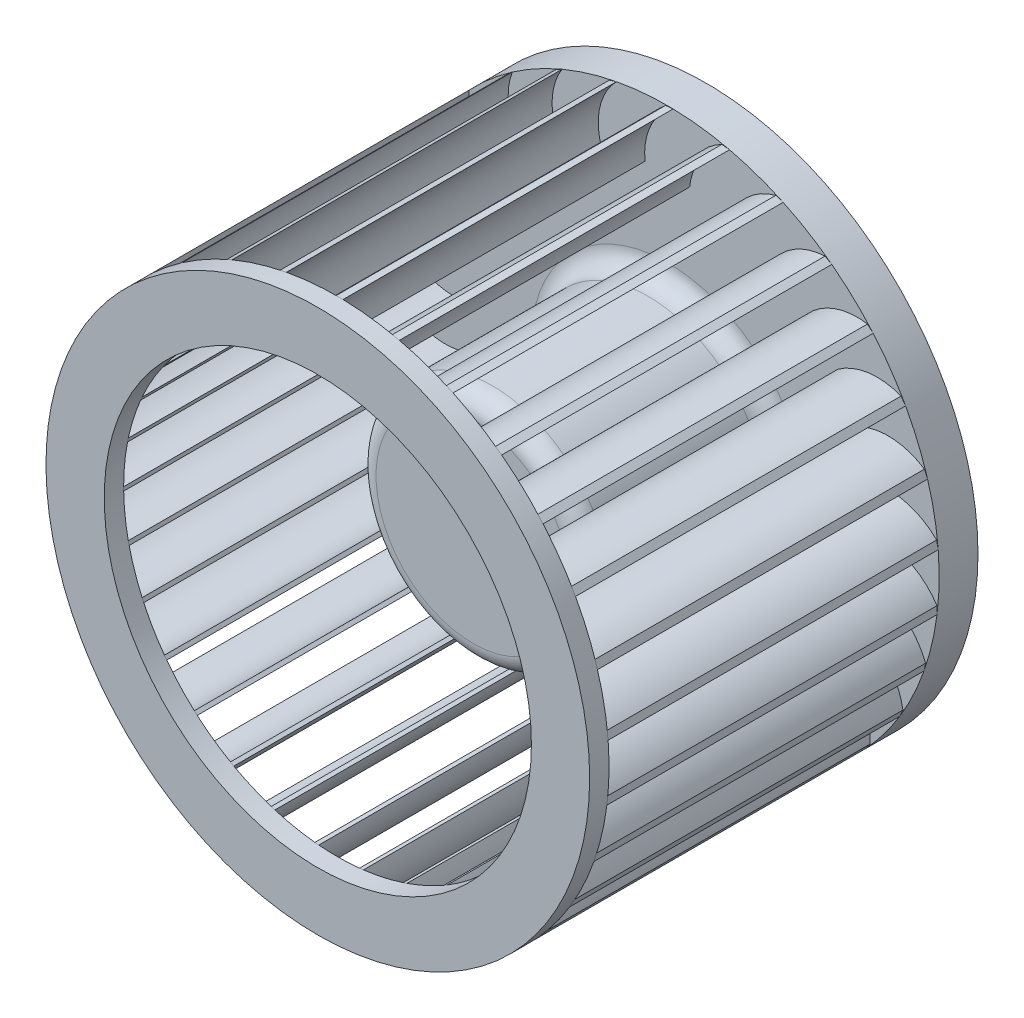
SolidWorks part; units mm, degrees
material "Silicon"
ref_plane "Front Plane" through (0, 0, 0) normal (0, 0, 1) x (1, 0, 0)
ref_plane "Top Plane" through (0, 0, 0) normal (0, 1, 0) x (1, 0, 0)
ref_plane "Right Plane" through (0, 0, 0) normal (1, 0, 0) x (0, 0, -1)
sketch "Sketch1" plane through (0, 0, 0) normal (0, 0, 1) x (1, 0, 0)
  circle A0 centre (0, 0) radius 14 construction
  dimension "D1" = 28
sketch "Sketch2" plane through (0, 0, 0) normal (0, 0, 1) x (1, 0, 0)
  circle A0 centre (0, 0) radius 14
  dimension "D1" = 28
extrude "Boss-Extrude1" add sketch "Sketch2" along normal blind 2
ref_plane "Plane1" through (0, 14, 0) normal (0, 1, 0) x (1, 0, 0)
ref_plane "Plane3" through (0, 13, 0) normal (0, 1, 0) x (1, 0, 0)
sketch "Sketch3" plane through (0, 13, 0) normal (0, 1, 0) x (1, 0, 0)
  line L0 (-14, -2) -> (14, -2) construction
  arc A0 (0, 0) -> (0, -2) centre (-36, -1) cw
  arc A1 (0, 0) -> (0, -2) centre (-54.9909, -1) cw
  dimension "D2" = 55
  dimension "D1" = 36
ref_plane "Plane2" through (0, 25, 0) normal (0, 1, 0) x (1, 0, 0)
sketch "Sketch4" plane through (0, 25, 0) normal (0, 1, 0) x (1, 0, 0)
  arc A0 (0, 0) -> (0, -2) centre (-32.2345, -1) cw
  arc A1 (0, 0) -> (0, -2) centre (-44.7388, -1) cw
  dimension "D1" = 32.25
  dimension "D2" = 44.75
sketch "Sketch5" plane through (0, 0, 2) normal (0, 0, 1) x (1, 0, 0)
  line L0 (0.0091, 13) -> (0, 13) construction
  line L1 (0, 0) -> (0, 13) construction
  line L2 (0, 13) -> (0, 14) construction
  line L3 (3.3352, 20.4911) -> (-3.3352, 5.5089) construction
  circle A0 centre (0, 0) radius 14 construction
  spline S0 degree 2 poles (0, 13) (1.6676, 16.7455) (0, 14) knots 0 0 0 1 1 1
  dimension "D1" = 8.2
  dimension "D2" = 24
sketch "Sketch6" plane through (0, 0, 0) normal (0, 0, -1) x (-1, 0, 0)
  circle A0 centre (0, 0) radius 14
  dimension "D1" = 28
sketch "Sketch7" plane through (0, 0, 2) normal (0, 0, 1) x (1, 0, 0)
  circle A0 centre (0, 0) radius 6
  dimension "D1" = 12
extrude "Boss-Extrude2" add sketch "Sketch7" along normal blind 10
sketch "Sketch8" plane through (0, 0, 2) normal (0, 0, 1) x (1, 0, 0)
  line L0 (0, 0) -> (14, 0) construction
  line L1 (13.8888, -1.7609) -> (13.8888, -1.3639)
  line L2 (11, 0) -> (11, 0.2)
  circle A0 centre (0, 0) radius 14 construction
  arc A1 (11, 0) -> (13.8888, -1.7609) centre (11, -3.25) cw
  arc A3 (11, 0.2) -> (13.8888, -1.3639) centre (11, -3.25) cw
  arc A4 (11, 0.2) -> (14.0666, -1.6693) centre (11, -3.25) cw construction
  dimension "D1" = 3.25
  dimension "D2" = 11
  dimension "D3" = 0.2
extrude "Boss-Extrude3" add sketch "Sketch8" along normal blind 17
pattern_circular "CirPattern1" count 30 over 360 about axis through (0, 0, 0) along (0, 0, 1) of "Boss-Extrude3"
sketch "Sketch9" plane through (0, 0, 19) normal (0, 0, 1) x (1, 0, 0)
  circle A0 centre (0, 0) radius 14
  circle A1 centre (0, 0) radius 14 construction
  circle A2 centre (0, 0) radius 11
extrude "Boss-Extrude4" add sketch "Sketch9" along normal blind 1
fillet "Fillet1" radius 1 2 edges at (6, 0, 12) (6, 0, 2)
